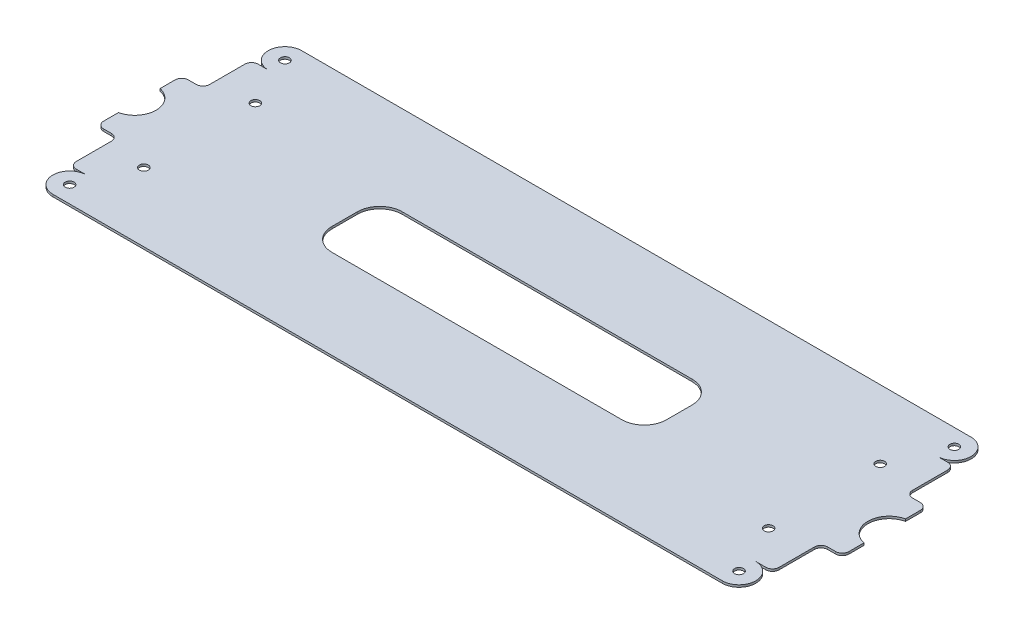
SolidWorks part; units mm, degrees
ref_plane "Front Plane" through (0, 0, 0) normal (0, 0, 1) x (1, 0, 0)
ref_plane "Top Plane" through (0, 0, 0) normal (0, 1, 0) x (1, 0, 0)
ref_plane "Right Plane" through (0, 0, 0) normal (1, 0, 0) x (0, 0, -1)
sketch "Sketch1" plane through (0, 0, 0) normal (0, 1, 0) x (1, 0, 0)
  line L1 (-157.5, 40.75) -> (157.5, 40.75) construction
  line L2 (-157.5, 40.75) -> (-157.5, -40.75) construction
  line L3 (-157.5, -40.75) -> (157.5, -40.75) construction
  line L4 (157.5, 40.75) -> (157.5, -40.75) construction
  line L5 (-157.5, 40.75) -> (157.5, -40.75) construction
  line L6 (-157.5, -40.75) -> (157.5, 40.75) construction
  line L19 (154.5, -37.75) -> (-154.5, -37.75) construction
  line L20 (154.5, -37.75) -> (154.5, 37.75) construction
  line L21 (154.5, 37.75) -> (-154.5, 37.75) construction
  line L22 (-154.5, -37.75) -> (-154.5, 37.75) construction
  line L23 (154.5, -37.75) -> (-154.5, 37.75) construction
  line L24 (154.5, 37.75) -> (-154.5, -37.75) construction
  line L25 (150, 55.75) -> (-150, 55.75)
  line L28 (-167.025, 19) -> (-167.025, 9.3127)
  line L31 (-150, -55.75) -> (150, -55.75)
  line L34 (167.025, -19) -> (167.025, -9.3127)
  line L36 (-157.5, 0) -> (-167.025, 0) construction
  line L37 (157.5, 0) -> (167.025, 0) construction
  line L38 (-157.5, 37.75) -> (-154.5, 37.75) construction
  line L43 (-167.025, 0) -> (-169.025, 0) construction
  line L44 (-167.025, -9.3127) -> (-167.025, -19)
  line L45 (-154.5, 37.75) -> (-154.5, 40.75) construction
  line L46 (-154.5, -40.75) -> (-154.5, -37.75) construction
  line L47 (-154.5, -37.75) -> (-157.5, -37.75) construction
  line L48 (154.5, -40.75) -> (154.5, -37.75) construction
  line L49 (154.5, -37.75) -> (157.5, -37.75) construction
  line L50 (154.5, 37.75) -> (154.5, 40.75) construction
  line L51 (157.5, 37.75) -> (154.5, 37.75) construction
  line L54 (-167.025, 19) -> (-157.5, 19)
  line L55 (-157.5, 19) -> (-157.5, 37.75)
  line L56 (-167.025, -19) -> (-157.5, -19)
  line L57 (-157.5, -19) -> (-157.5, -37.75)
  line L62 (167.025, -19) -> (157.5, -19)
  line L63 (157.5, -19) -> (157.5, -37.75)
  line L64 (167.025, 19) -> (157.5, 19)
  line L65 (157.5, 19) -> (157.5, 37.75)
  line L68 (0, 48.25) -> (0, 0) construction
  line L69 (150, 0) -> (0, 0) construction
  line L70 (-167.025, 9.3127) -> (-167.025, 0) construction
  line L71 (-150, 48.25) -> (150, 48.25) construction
  line L72 (-150, 48.25) -> (-150, -48.25) construction
  line L73 (-150, -48.25) -> (150, -48.25) construction
  line L74 (150, 48.25) -> (150, -48.25) construction
  line L75 (-167.025, 0) -> (-167.025, -9.3127) construction
  line L76 (169.025, 0) -> (167.025, 0) construction
  line L77 (167.025, 9.3127) -> (167.025, 19)
  line L78 (167.025, 9.3127) -> (167.025, 0) construction
  line L79 (167.025, 0) -> (167.025, -9.3127) construction
  line L80 (-150, 55.75) -> (-150, 40.75) construction
  line L81 (150, 55.75) -> (150, 40.75) construction
  line L82 (-150, -55.75) -> (-150, -40.75) construction
  line L83 (150, -55.75) -> (150, -40.75) construction
  line L84 (-154.5, -40.75) -> (-150, -40.75)
  line L85 (-154.5, 40.75) -> (-150, 40.75)
  line L86 (150, 40.75) -> (154.5, 40.75)
  line L87 (150, -40.75) -> (154.5, -40.75)
  line L88 (-157.5, -48.25) -> (-157.5, -37.75) construction
  line L89 (-159.5, 0) -> (0, 0) construction
  line L91 (-140, 25) -> (140, 25) construction
  line L92 (-140, 25) -> (-140, -25) construction
  line L93 (-140, -25) -> (140, -25) construction
  line L94 (140, 25) -> (140, -25) construction
  line L95 (-140, 25) -> (140, -25) construction
  line L96 (-140, -25) -> (140, 25) construction
  line L97 (-75, 15.75) -> (75, 15.75)
  line L98 (-75, 15.75) -> (-75, -15.75)
  line L99 (-75, -15.75) -> (75, -15.75)
  line L100 (75, 15.75) -> (75, -15.75)
  line L101 (-75, 15.75) -> (75, -15.75) construction
  line L102 (-75, -15.75) -> (75, 15.75) construction
  arc A0 (-154.5, 40.75) -> (-157.5, 37.75) centre (-154.5, 37.75) ccw
  arc A1 (-157.5, -37.75) -> (-154.5, -40.75) centre (-154.5, -37.75) ccw
  arc A2 (154.5, -40.75) -> (157.5, -37.75) centre (154.5, -37.75) ccw
  arc A3 (154.5, 40.75) -> (157.5, 37.75) centre (154.5, 37.75) cw
  circle A8 centre (-150, 48.25) radius 2
  circle A9 centre (150, 48.25) radius 2
  circle A10 centre (150, -48.25) radius 2
  circle A11 centre (-150, -48.25) radius 2
  circle A12 centre (-169.025, 0) radius 9.525 construction
  arc A13 (-167.025, -9.3127) -> (-167.025, 9.3127) centre (-169.025, 0) ccw
  circle A14 centre (169.025, 0) radius 9.525 construction
  arc A15 (167.025, 9.3127) -> (167.025, -9.3127) centre (169.025, 0) ccw
  arc A16 (150, 40.75) -> (150, 55.75) centre (150, 48.25) ccw
  arc A17 (-150, 55.75) -> (-150, 40.75) centre (-150, 48.25) ccw
  arc A18 (-150, -40.75) -> (-150, -55.75) centre (-150, -48.25) ccw
  arc A19 (150, -40.75) -> (150, -55.75) centre (150, -48.25) cw
  circle A24 centre (-140, 25) radius 2
  circle A25 centre (-140, -25) radius 2
  circle A26 centre (140, -25) radius 2
  circle A27 centre (140, 25) radius 2
  point P0 (0, 0)
  point P5 (0, 0)
  point P31 (0, 0)
  point P45 (-159.5, 0)
  point P50 (159.5, 0)
  dimension "D5" = 38
  dimension "D9" = 19.05
  dimension "D11" = 10
  dimension "D16" = 2
  dimension "D13" = 4
  dimension "D18" = 19.05
  dimension "D6" = 50
  dimension "D14" = 25
  dimension "D3" = 4
  dimension "D1" = 81.5
  dimension "D2" = 300
  dimension "D4" = 3
  dimension "D7" = 38
  dimension "D8" = 2
  dimension "D10" = 15
  dimension "D12" = 2
  dimension "D15" = 75
  dimension "D17" = 2
extrude "Boss-Extrude1" add sketch "Sketch1" along normal blind 1
fillet "Fillet1" radius 10 4 edges at (75, 0.5, 15.75) (75, 0.5, -15.75) (-75, 0.5, -15.75) (-75, 0.5, 15.75)
fillet "Fillet2" radius 3 8 edges at (167.025, 0.5, -19) (157.5, 0.5, -19) (157.5, 0.5, 19) (167.025, 0.5, 19) (-157.5, 0.5, -19) (-167.025, 0.5, -19) (-157.5, 0.5, 19) (-167.025, 0.5, 19)
pattern_linear "LPattern1" [suppressed] count 9 spacing 115 count 2 spacing 340
